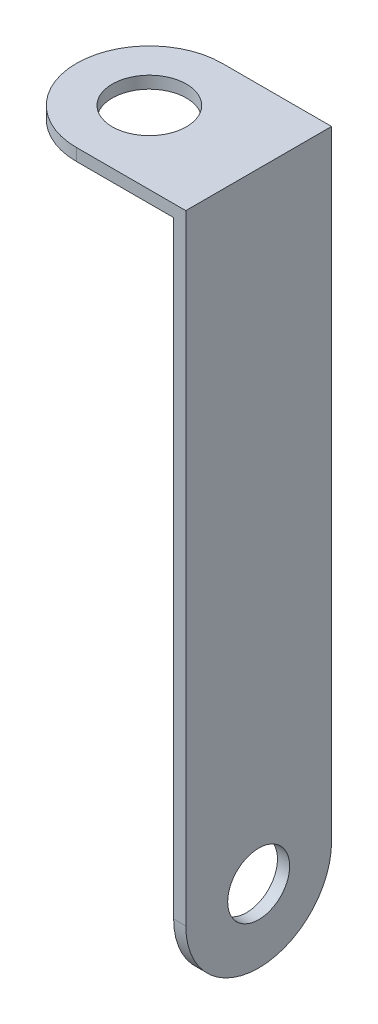
SolidWorks part; units mm, degrees
ref_plane "Front Plane" through (0, 0, 0) normal (0, 0, 1) x (1, 0, 0)
ref_plane "Top Plane" through (0, 0, 0) normal (0, 1, 0) x (1, 0, 0)
ref_plane "Right Plane" through (0, 0, 0) normal (1, 0, 0) x (0, 0, -1)
sketch "Sketch1" plane through (0, 0, 0) normal (0, 1, 0) x (1, 0, 0)
  line L0 (0, 6) -> (9, 6)
  line L3 (9, 6) -> (9, -6)
  line L4 (9, -6) -> (0, -6)
  circle A2 centre (0, 0) radius 3.05
  arc A4 (0, 6) -> (0, -6) centre (0, 0) ccw
  circle A5 centre (0, 0) radius 5 construction
  point P6 (-15.9381, 2.1528)
  dimension "D2" = 9
  dimension "D3" = 6.1
  dimension "D1" = 12
  dimension "D4" = 10
extrude "Boss-Extrude1" add sketch "Sketch1" along normal blind 1
sketch "Sketch3" plane through (0, 0, 0) normal (1, 0, 0) x (0, 0, -1)
  line L0 (0, 0) -> (0, -50) construction
  line L1 (-6, 0) -> (6, 0)
  line L2 (-6, 0) -> (-6, -50)
  line L4 (6, 0) -> (6, -50)
  circle A0 centre (0, -50) radius 2.55
  arc A1 (-6, -50) -> (6, -50) centre (0, -50) ccw
  point P10 (-6, -15.7942)
  point P11 (6, -15.7942)
  dimension "D1" = 12
  dimension "D2" = 5.1
  dimension "D3" = 50
extrude "Boss-Extrude2" add sketch "Sketch3" against normal blind 1 from surface at 9 starting at face at (9, 0.5, 0)
